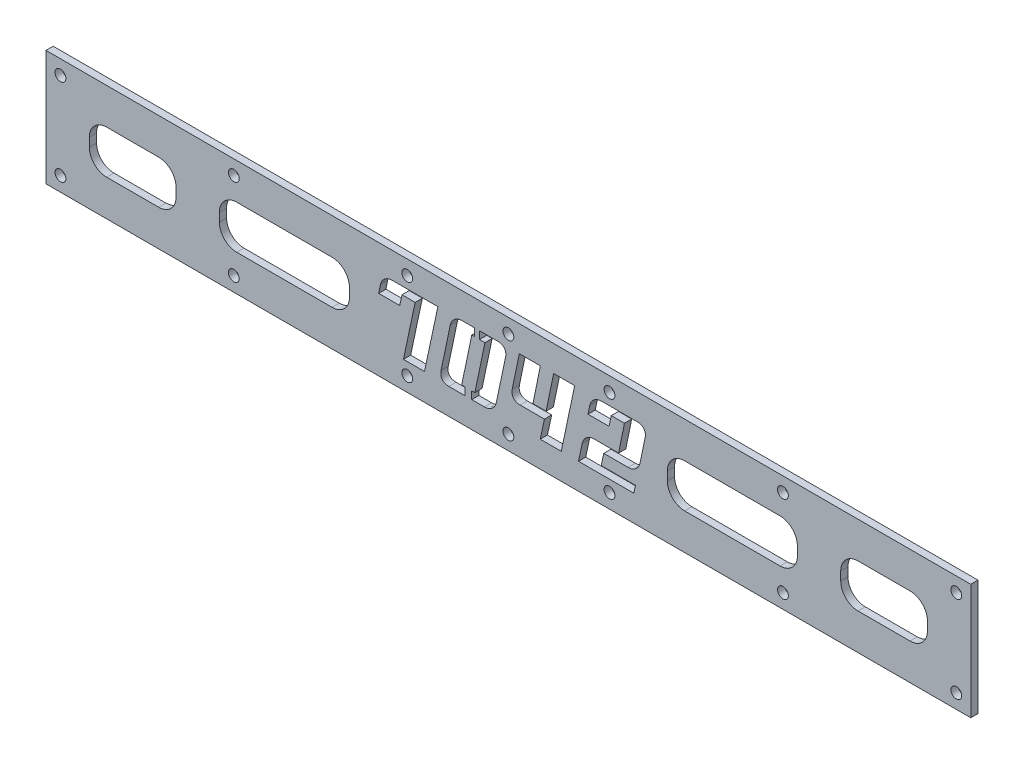
SolidWorks part; units mm, degrees
ref_plane "Front Plane" through (0, 0, 0) normal (0, 0, 1) x (1, 0, 0)
ref_plane "Top Plane" through (0, 0, 0) normal (0, 1, 0) x (1, 0, 0)
ref_plane "Right Plane" through (0, 0, 0) normal (1, 0, 0) x (0, 0, -1)
sketch "Sketch1" plane through (0, 0, 0) normal (0, 0, 1) x (1, 0, 0)
  line L1 (-203.2, 25.4) -> (203.2, 25.4)
  line L2 (-203.2, 25.4) -> (-203.2, -25.4)
  line L3 (-203.2, -25.4) -> (203.2, -25.4)
  line L4 (203.2, 25.4) -> (203.2, -25.4)
  line L5 (-203.2, 25.4) -> (203.2, -25.4) construction
  line L6 (-203.2, -25.4) -> (203.2, 25.4) construction
  point P0 (0, 0)
  dimension "D1" = 50.8
  dimension "D2" = 406.4
extrude "Boss-Extrude1" add sketch "Sketch1" along normal blind 3.175
sketch "Sketch2" plane through (0, 0, 3.175) normal (0, 0, 1) x (1, 0, 0)
  line L0 (-203.2, -13.97) -> (203.2, -13.97) construction
  line L1 (-203.2, 25.4) -> (-203.2, -25.4) construction
  line L2 (203.2, -25.4) -> (203.2, 25.4) construction
  line L3 (-203.2, -25.4) -> (203.2, -25.4) construction
  text T0 "7042" font "Aero" height 27.94
  point P15 (-12.6554, 14.7416)
  point P16 (-16.519, 14.7416)
  dimension "D1" = 11.43
extrude "Cut-Extrude1" cut sketch "Sketch2" against normal blind 3.175
sketch "Sketch3" plane through (0, 0, 3.175) normal (0, 0, 1) x (1, 0, 0)
  line L1 (-14.9024, 18.3116) -> (-12.6865, 18.3116)
  line L2 (-14.9024, 18.3116) -> (-14.9024, 6.8776)
  line L3 (-14.9024, 6.8776) -> (-12.6865, 6.8776)
  line L4 (-12.6865, 18.3116) -> (-12.6865, 6.8776)
  line L5 (-19.1202, -9.837) -> (-16.1087, -9.837)
  line L6 (-19.1202, -9.837) -> (-19.1202, -21.6653)
  line L7 (-19.1202, -21.6653) -> (-16.1087, -21.6653)
  line L8 (-16.1087, -9.837) -> (-16.1087, -21.6653)
extrude "Boss-Extrude2" add sketch "Sketch3" against normal blind 3.175
sketch "Sketch4" plane through (0, 0, 3.175) normal (0, 0, 1) x (1, 0, 0)
  line L0 (-203.2, -25.4) -> (203.2, -25.4) construction
  line L1 (-184.15, 9.525) -> (-146.05, 9.525)
  line L2 (-184.15, 9.525) -> (-184.15, -9.525)
  line L3 (-184.15, -9.525) -> (-146.05, -9.525)
  line L4 (-146.05, 9.525) -> (-146.05, -9.525)
  line L5 (-127, 9.525) -> (-69.85, 9.525)
  line L6 (-127, 9.525) -> (-127, -9.525)
  line L7 (-127, -9.525) -> (-69.85, -9.525)
  line L8 (-69.85, 9.525) -> (-69.85, -9.525)
  line L9 (-203.2, 25.4) -> (-203.2, -25.4) construction
  line L10 (0, 25.4) -> (0, -25.4) construction
  line L11 (203.2, 25.4) -> (-203.2, 25.4) construction
  line L12 (69.85, 9.525) -> (69.85, -9.525)
  line L13 (127, -9.525) -> (69.85, -9.525)
  line L14 (127, 9.525) -> (127, -9.525)
  line L15 (127, 9.525) -> (69.85, 9.525)
  line L16 (146.05, 9.525) -> (146.05, -9.525)
  line L17 (184.15, -9.525) -> (146.05, -9.525)
  line L18 (184.15, 9.525) -> (184.15, -9.525)
  line L19 (184.15, 9.525) -> (146.05, 9.525)
  dimension "D1" = 19.05
  dimension "D2" = 15.875
  dimension "D3" = 38.1
  dimension "D4" = 57.15
  dimension "D5" = 19.05
  dimension "D6" = 19.05
extrude "Cut-Extrude2" cut sketch "Sketch4" against normal blind 3.175
fillet "Fillet1" radius 7.62 16 edges at (184.15, -9.525, 1.5875) (184.15, 9.525, 1.5875) (146.05, -9.525, 1.5875) (146.05, 9.525, 1.5875) (127, -9.525, 1.5875) (127, 9.525, 1.5875) (69.85, -9.525, 1.5875) (69.85, 9.525, 1.5875) (-69.85, -9.525, 1.5875) (-69.85, 9.525, 1.5875) (-127, -9.525, 1.5875) (-127, 9.525, 1.5875) (-184.15, -9.525, 1.5875) (-146.05, -9.525, 1.5875) (-146.05, 9.525, 1.5875) (-184.15, 9.525, 1.5875)
sketch "Sketch5" plane through (0, 0, 3.175) normal (0, 0, 1) x (1, 0, 0)
  line L0 (203.2, 25.4) -> (-203.2, 25.4) construction
  line L1 (-203.2, 25.4) -> (-203.2, -25.4) construction
  line L2 (0, 25.4) -> (0, -25.4) construction
  line L3 (-203.2, -25.4) -> (203.2, -25.4) construction
  line L4 (-203.2, 0) -> (203.2, 0) construction
  line L5 (203.2, -25.4) -> (203.2, 25.4) construction
  circle A0 centre (-196.85, 19.05) radius 2.3813
  circle A1 centre (-120.65, 19.05) radius 2.3813
  circle A2 centre (-44.45, 19.05) radius 2.3813
  circle A4 centre (0, 19.05) radius 2.3813
  circle A5 centre (44.45, 19.05) radius 2.3813
  circle A6 centre (120.65, 19.05) radius 2.3813
  circle A7 centre (196.85, 19.05) radius 2.3813
  circle A8 centre (196.85, -19.05) radius 2.3813
  circle A9 centre (120.65, -19.05) radius 2.3813
  circle A10 centre (44.45, -19.05) radius 2.3813
  circle A11 centre (0, -19.05) radius 2.3813
  circle A13 centre (-44.45, -19.05) radius 2.3813
  circle A14 centre (-120.65, -19.05) radius 2.3813
  circle A15 centre (-196.85, -19.05) radius 2.3813
  point P11 (0, 20.902)
  dimension "D1" = 4.7625
  dimension "D2" = 6.35
  dimension "D3" = 6.35
  dimension "D5" = 6.35
  dimension "D4" = 3
extrude "Cut-Extrude3" cut sketch "Sketch5" against normal blind 43.18
